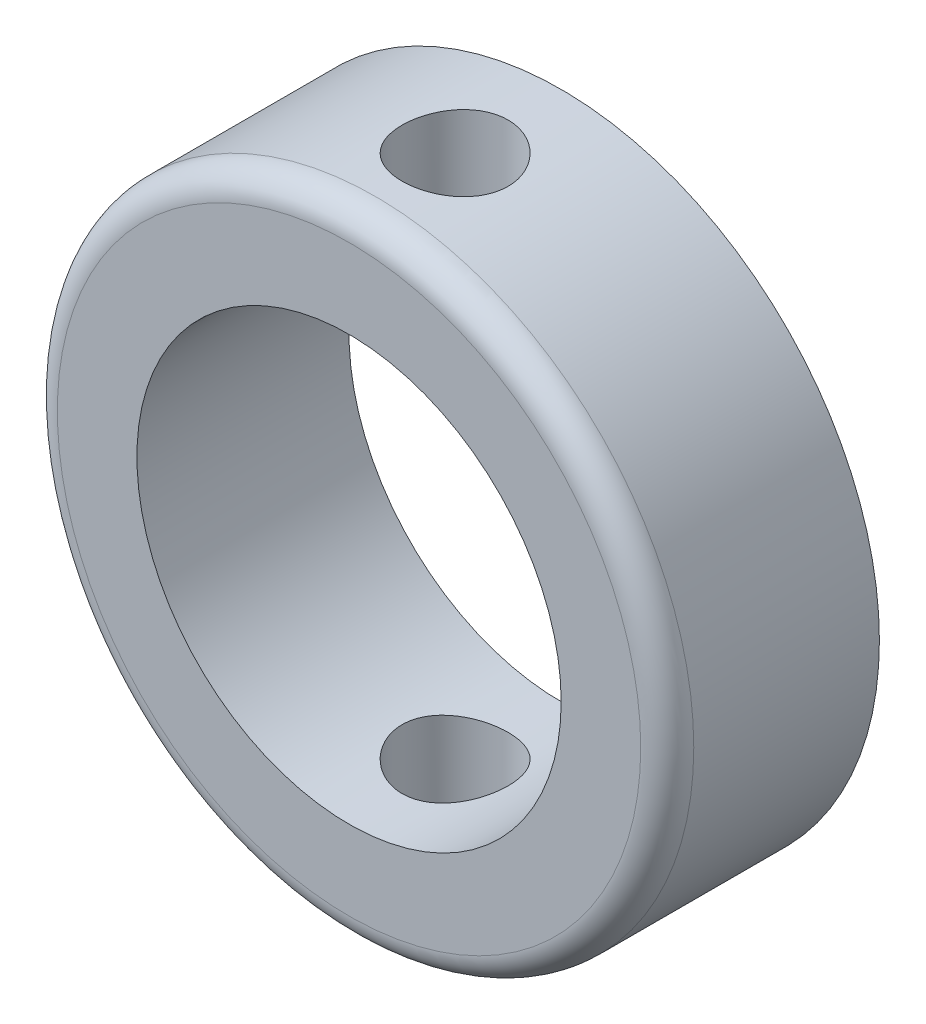
SolidWorks part; units mm, degrees
ref_plane "Front Plane" through (0, 0, 0) normal (0, 0, 1) x (1, 0, 0)
ref_plane "Top Plane" through (0, 0, 0) normal (0, 1, 0) x (1, 0, 0)
ref_plane "Right Plane" through (0, 0, 0) normal (1, 0, 0) x (0, 0, -1)
sketch "Sketch1" plane through (0, 0, 0) normal (0, 0, 1) x (1, 0, 0)
  circle A0 centre (0, 0) radius 8
  circle A1 centre (0, 0) radius 12
  dimension "D1" = 16
  dimension "D2" = 24
extrude "Boss-Extrude1" add sketch "Sketch1" along normal mid plane 8
fillet "Fillet1" radius 1 1 edges at (12, 0, 4)
sketch "Sketch3" plane through (0, 0, 0) normal (0, 1, 0) x (1, 0, 0)
  circle A0 centre (0, 0) radius 2
  dimension "D1" = 4
extrude "Cut-Extrude1" cut sketch "Sketch3" against normal mid plane 100
